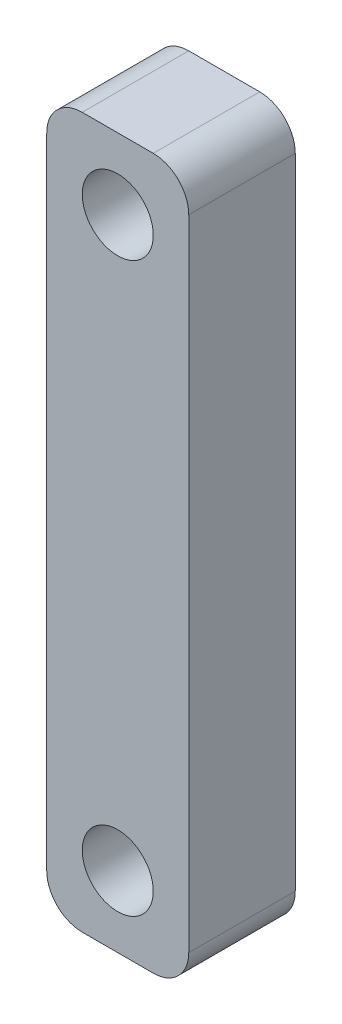
SolidWorks part; units mm, degrees
ref_plane "Plan de face" through (0, 0, 0) normal (0, 0, 1) x (1, 0, 0)
ref_plane "Plan de dessus" through (0, 0, 0) normal (0, 1, 0) x (1, 0, 0)
ref_plane "Plan de droite" through (0, 0, 0) normal (1, 0, 0) x (0, 0, -1)
sketch "Esquisse1" plane through (0, 0, 0) normal (0, 0, 1) x (1, 0, 0)
  line L1 (0, 0) -> (4, 0)
  line L2 (0, 0) -> (0, 20)
  line L3 (0, 20) -> (4, 20)
  line L4 (4, 0) -> (4, 20)
  dimension "D1" = 4
  dimension "D2" = 20
extrude "Boss.-Extru.1" add sketch "Esquisse1" along normal blind 3
sketch "Esquisse3" plane through (0, 0, 3) normal (0, 0, 1) x (1, 0, 0)
  line L0 (0, 0) -> (4, 0) construction
  line L1 (0, 20) -> (0, 0) construction
  line L2 (4, 20) -> (0, 20) construction
  circle A0 centre (2, 2) radius 1
  circle A1 centre (2, 18) radius 1
  point P2 (2, 0)
  dimension "D1" = 2
  dimension "D3" = 2
  dimension "D2" = 2
extrude "Enlèv. mat.-Extru.1" cut sketch "Esquisse3" against normal blind 6
fillet "Congé4" radius 1 1 edges at (4, 0, 1.5)
fillet "Congé5" radius 1 1 edges at (0, 0, 1.5)
fillet "Congé6" radius 1 1 edges at (0, 20, 1.5)
fillet "Congé7" radius 1 1 edges at (4, 20, 1.5)
